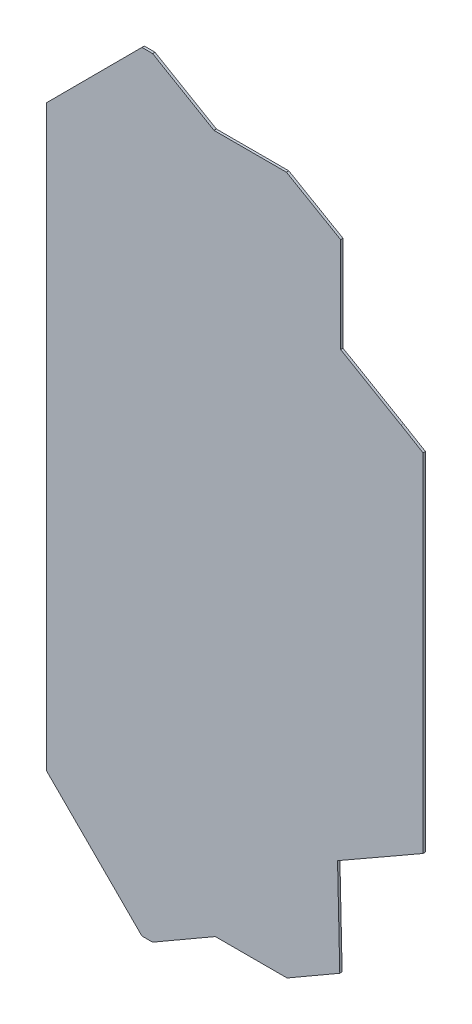
SolidWorks part; units mm, degrees
ref_plane "Front Plane" through (0, 0, 0) normal (0, 0, 1) x (1, 0, 0)
ref_plane "Top Plane" through (0, 0, 0) normal (0, 1, 0) x (1, 0, 0)
ref_plane "Right Plane" through (0, 0, 0) normal (1, 0, 0) x (0, 0, -1)
sketch "Sketch1" plane through (0, 0, 0) normal (0, 0, 1) x (1, 0, 0)
  line L1 (361.63, -374.4545) -> (380.1374, -385.4821)
  line L3 (380.1374, -385.4821) -> (380.1374, -677.6551)
  line L4 (380.1374, -677.6551) -> (308.13, -718.8741)
  line L5 (308.13, -718.8741) -> (310.0061, -800.0658)
  line L7 (310.0061, -800.0658) -> (265.6237, -825.69)
  line L8 (265.6237, -825.69) -> (205.2099, -825.69)
  line L9 (205.2099, -825.69) -> (152.401, -856.1792)
  line L11 (152.401, -856.1792) -> (143.4082, -856.1792)
  line L12 (143.4082, -856.1792) -> (63.137, -775.908)
  line L14 (63.137, -775.908) -> (63.137, -288.673)
  line L15 (63.137, -288.673) -> (143.4082, -208.1788)
  line L17 (143.4082, -208.1788) -> (152.401, -208.1788)
  line L18 (152.401, -208.1788) -> (204.0954, -238.3558)
  line L19 (204.0954, -238.3558) -> (265.083, -238.3558)
  line L21 (265.083, -238.3558) -> (310.7286, -264.7093)
  line L22 (310.7286, -264.7093) -> (310.7286, -344.8785)
  line L23 (310.7286, -344.8785) -> (361.63, -374.4545)
extrude "Boss-Extrude1" add sketch "Sketch1" along normal blind 2 contours L14 L15 L17 L18 L19 L21 L22 L23 L1 L3 L4 L5 L7 L8 L9 L11 L12
